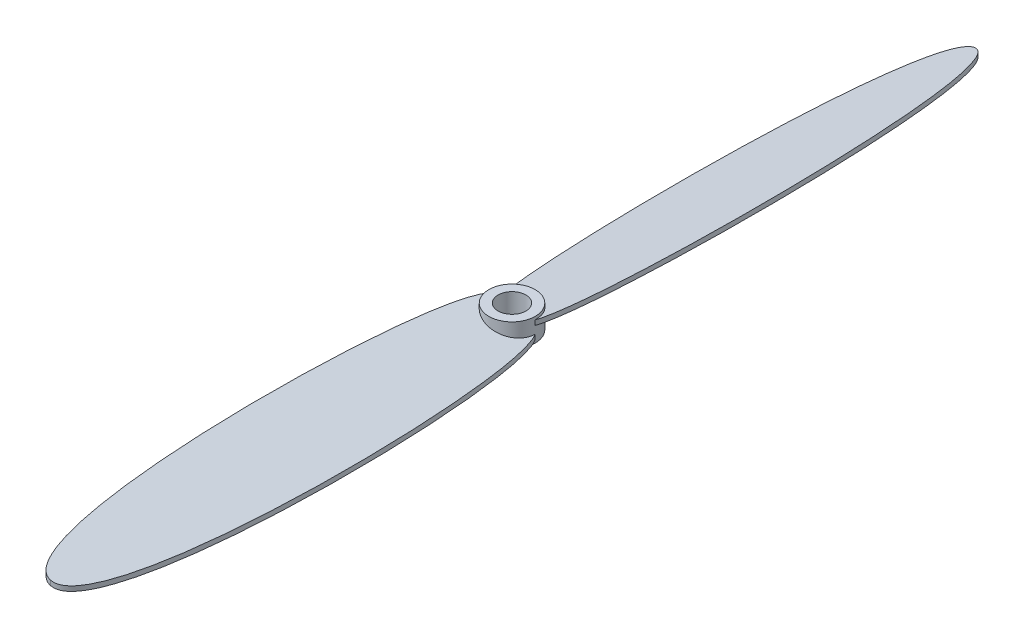
SolidWorks part; units mm, degrees
ref_plane "前基準面" through (0, 0, 0) normal (0, 0, 1) x (1, 0, 0)
ref_plane "上基準面" through (0, 0, 0) normal (0, 1, 0) x (1, 0, 0)
ref_plane "右基準面" through (0, 0, 0) normal (1, 0, 0) x (0, 0, -1)
sketch "草圖1" plane through (0, 0, 0) normal (0, 1, 0) x (1, 0, 0)
  circle A0 centre (0, 0) radius 3
  circle A1 centre (0, 0) radius 5
  dimension "D1" = 6
  dimension "D2" = 10
extrude "填料-伸長1" add sketch "草圖1" along normal blind 5
sketch "草圖9" plane through (0, 5, 0) normal (0, 1, 0) x (1, 0, 0)
  line L0 (0, 0) -> (5, 0) construction
  line L1 (-9.5, 99.5) -> (9.5, 99.5) construction
  line L2 (-9.5, 99.5) -> (-9.5, -99.5) construction
  line L3 (-9.5, -99.5) -> (9.5, -99.5) construction
  line L4 (9.5, 99.5) -> (9.5, -99.5) construction
  line L5 (-9.5, 99.5) -> (9.5, -99.5) construction
  line L6 (-9.5, -99.5) -> (9.5, 99.5) construction
  line L7 (0, 99.5) -> (0, 0) construction
  circle A0 centre (0, 0) radius 5 construction
  spline S0 degree 3 poles (5, 0) (10.5156, 9.3195) (11.321, 99.5) (0, 99.5) knots 0 0 0 0 1 1 1 1
  spline S1 degree 3 poles (-5, 0) (-10.5156, 9.3195) (-11.321, 99.5) (0, 99.5) knots 0 0 0 0 1 1 1 1
  spline S2 degree 3 poles (5, 0) (10.5156, -9.3195) (11.321, -99.5) (0, -99.5) knots 0 0 0 0 1 1 1 1
  spline S3 degree 3 poles (-5, 0) (-10.5156, -9.3195) (-11.321, -99.5) (0, -99.5) knots 0 0 0 0 1 1 1 1
  point P0 (0, 0)
  dimension "D1" = 199
  dimension "D2" = 19
sketch "草圖6" plane through (0, 0, 0) normal (0, 0, 1) x (1, 0, 0)
  line L0 (-5, 3.8397) -> (5, 1.1603) construction
  line L2 (0, 5) -> (0, 0) construction
  line L3 (3, 5) -> (-3, 5) construction
  line L4 (9.6593, -0.0882) -> (-9.6593, 5.0882) construction
  line L5 (9.5298, -0.5712) -> (-9.7887, 4.6052)
  line L6 (9.7887, 0.3948) -> (-9.5298, 5.5712)
  arc A0 (9.5298, -0.5712) -> (9.7887, 0.3948) centre (9.6593, -0.0882) ccw
  arc A1 (-9.5298, 5.5712) -> (-9.7887, 4.6052) centre (-9.6593, 5.0882) ccw
  point P2 (0, 2.5)
  point P12 (0, 2.5)
  dimension "D1" = 75
  dimension "D2" = 1
  dimension "D3" = 20
extrude "填料-伸長7" add sketch "草圖6" along normal blind 100
sketch "草圖7" plane through (0, 0, 0) normal (0, 0, 1) x (1, 0, 0)
  line L0 (9.2834, 4.9875) -> (-9.2834, 0.0125) construction
  line L1 (0, 0) -> (0, 5) construction
  line L2 (3, 5) -> (-3, 5) construction
  line L3 (-9.6593, -0.0882) -> (9.6593, 5.0882) construction
  line L4 (-9.7887, 0.3948) -> (9.5298, 5.5712)
  line L5 (-9.5298, -0.5712) -> (9.7887, 4.6052)
  arc A0 (-9.7887, 0.3948) -> (-9.5298, -0.5712) centre (-9.6593, -0.0882) ccw
  arc A1 (9.7887, 4.6052) -> (9.5298, 5.5712) centre (9.6593, 5.0882) ccw
  point P7 (0, 2.5)
  point P10 (0, 2.5)
  dimension "D1" = 75
  dimension "D2" = 20
  dimension "D3" = 1
extrude "填料-伸長8" add sketch "草圖7" against normal blind 100
sketch "草圖8" plane through (0, 5, 0) normal (0, 1, 0) x (1, 0, 0)
  circle A0 centre (0, 0) radius 3 construction
  circle A1 centre (0, 0) radius 3
extrude "除料-伸長1" cut sketch "草圖8" against normal through all
extrude "除料-伸長2" cut sketch "草圖9" against normal through all and the other way through all flip side to cut
